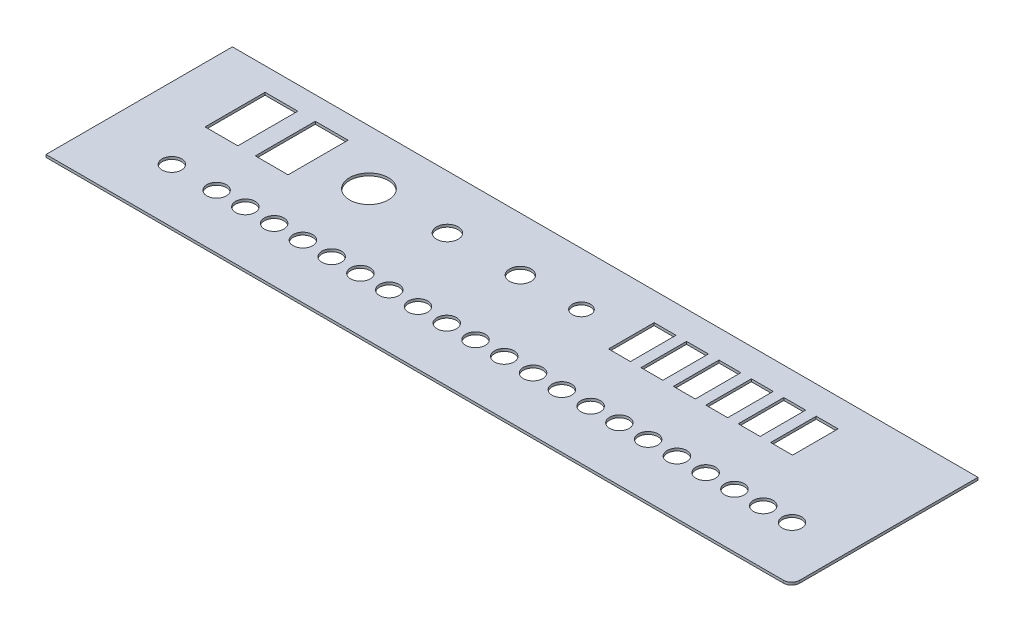
SolidWorks part; units mm, degrees
ref_plane "Front Plane" through (0, 0, 0) normal (0, 0, 1) x (1, 0, 0)
ref_plane "Top Plane" through (0, 0, 0) normal (0, 1, 0) x (1, 0, 0)
ref_plane "Right Plane" through (0, 0, 0) normal (1, 0, 0) x (0, 0, -1)
sketch "Boceto" plane through (0, 0, 0) normal (0, 1, 0) x (1, 0, 0)
  line L0 (-59.1, 30.6902) -> (-173.0029, 30.6902) construction
  line L5 (-59.1, -51.6098) -> (395.9, -51.6098) construction
  line L6 (-59.1, -51.6098) -> (-59.1, 63.3902) construction
  line L7 (-59.1, 63.3902) -> (395.9, 63.3902) construction
  line L8 (395.9, -51.6098) -> (395.9, 63.3902) construction
  line L9 (-28.6, 48.9902) -> (-8.6, 48.9902) construction
  line L10 (-28.6, 48.9902) -> (-28.6, 12.3902) construction
  line L11 (-28.6, 12.3902) -> (-8.6, 12.3902) construction
  line L12 (-8.6, 48.9902) -> (-8.6, 12.3902) construction
  line L13 (-28.6, 48.9902) -> (-8.6, 12.3902) construction
  line L14 (-28.6, 12.3902) -> (-8.6, 48.9902) construction
  line L15 (-59.1, -18.1098) -> (395.9, -18.1098) construction
  line L16 (2.4, 12.3902) -> (22.4, 12.3902) construction
  line L17 (2.4, 12.3902) -> (2.4, 48.9902) construction
  line L18 (2.4, 48.9902) -> (22.4, 48.9902) construction
  line L19 (22.4, 12.3902) -> (22.4, 48.9902) construction
  line L20 (2.4, 12.3902) -> (22.4, 48.9902) construction
  line L21 (2.4, 48.9902) -> (22.4, 12.3902) construction
  line L22 (174.9, 49.7902) -> (194.9, 49.7902) construction
  line L23 (174.9, 49.7902) -> (174.9, 11.7902) construction
  line L24 (174.9, 11.7902) -> (194.9, 11.7902) construction
  line L25 (194.9, 49.7902) -> (194.9, 11.7902) construction
  line L26 (174.9, 49.7902) -> (194.9, 11.7902) construction
  line L27 (174.9, 11.7902) -> (194.9, 49.7902) construction
  line L34 (211.4, 17.5561) -> (331, 17.5561) construction
  line L35 (211.4, 17.5561) -> (211.4, 46.5902) construction
  line L36 (211.4, 46.5902) -> (331, 46.5902) construction
  line L37 (331, 17.5561) -> (331, 46.5902) construction
  line L38 (211.4, 17.5561) -> (331, 46.5902) construction
  line L39 (211.4, 46.5902) -> (331, 17.5561) construction
  circle A0 centre (54.9, 29.6902) radius 11.1 construction
  circle A1 centre (102.75, 30.2402) radius 4.85 construction
  circle A2 centre (147.75, 30.2402) radius 4.85 construction
  circle A3 centre (-18.9, -18.1098) radius 6 construction
  circle A4 centre (8.7, -18.1098) radius 6 construction
  circle A5 centre (26.45, -18.1098) radius 6 construction
  circle A6 centre (44.2, -18.1098) radius 6 construction
  circle A7 centre (61.95, -18.1098) radius 6 construction
  circle A8 centre (79.7, -18.1098) radius 6 construction
  circle A9 centre (97.45, -18.1098) radius 6 construction
  circle A10 centre (115.2, -18.1098) radius 6 construction
  circle A11 centre (132.95, -18.1098) radius 6 construction
  circle A12 centre (150.7, -18.1098) radius 6 construction
  circle A13 centre (168.45, -18.1098) radius 6 construction
  circle A14 centre (186.2, -18.1098) radius 6 construction
  circle A15 centre (203.95, -18.1098) radius 6 construction
  circle A16 centre (221.7, -18.1098) radius 6 construction
  circle A17 centre (239.45, -18.1098) radius 6 construction
  circle A18 centre (257.2, -18.1098) radius 6 construction
  circle A19 centre (274.95, -18.1098) radius 6 construction
  circle A20 centre (292.7, -18.1098) radius 6 construction
  circle A21 centre (310.45, -18.1098) radius 6 construction
  circle A22 centre (328.2, -18.1098) radius 6 construction
  circle A23 centre (345.95, -18.1098) radius 6 construction
  circle A24 centre (363.7, -18.1098) radius 6 construction
  point P0 (0, 0)
  point P6 (-18.6, 30.6902)
  point P13 (12.4, 30.6902)
  point P24 (184.9, 30.7902)
  point P34 (271.2, 32.0731)
  point P40 (0, 0)
  point P41 (0, 0)
  dimension "D10" = 22.2
  dimension "D11" = 33.7
  dimension "D14" = 9.7
  dimension "D17" = 9.7
  dimension "D23" = 12
  dimension "D29" = 81.5
  dimension "D30" = 12
  dimension "D1" = 455
  dimension "D2" = 115
  dimension "D3" = 14.4
  dimension "D4" = 30.5
  dimension "D5" = 20
  dimension "D6" = 36.6
  dimension "D7" = 11
  dimension "D8" = 20
  dimension "D9" = 36.6
  dimension "D12" = 114
  dimension "D13" = 161.85
  dimension "D15" = 33.15
  dimension "D16" = 33.15
  dimension "D18" = 206.85
  dimension "D19" = 20
  dimension "D20" = 38
  dimension "D21" = 13.6
  dimension "D22" = 234
  dimension "D24" = 270.5
  dimension "D25" = 119.6
  dimension "D26" = 16.8
  dimension "D27" = 29.0341
  dimension "D28" = 40.2
  dimension "D31" = 27.6
  dimension "D32" = 21
sketch "Sketch4" plane through (0, 0, 0) normal (0, 1, 0) x (1, 0, 0)
  line L0 (-28.6, 48.9902) -> (-8.6, 12.3902) construction
  line L1 (-60.5474, 63.3902) -> (394.4526, 63.3902)
  line L3 (-60.5474, -51.6098) -> (391.9526, -51.6098)
  line L5 (-28.7093, 12.1902) -> (-8.4907, 12.1902)
  line L6 (-28.7093, 12.1902) -> (-28.7093, 49.1902)
  line L7 (-28.7093, 49.1902) -> (-8.4907, 49.1902)
  line L8 (-8.4907, 12.1902) -> (-8.4907, 49.1902)
  line L9 (-28.7093, 12.1902) -> (-8.4907, 49.1902) construction
  line L10 (-28.7093, 49.1902) -> (-8.4907, 12.1902) construction
  line L11 (-28.6, 12.3902) -> (-8.6, 48.9902) construction
  line L12 (2.4, 12.3902) -> (22.4, 48.9902) construction
  line L17 (2.2907, 12.1902) -> (2.2907, 49.1902)
  line L18 (2.2907, 12.1902) -> (22.5093, 12.1902)
  line L19 (22.5093, 12.1902) -> (22.5093, 49.1902)
  line L20 (2.2907, 49.1902) -> (22.5093, 49.1902)
  line L21 (102.75, 30.2402) -> (199.8359, 30.2402) construction
  line L22 (211.4, 32.0731) -> (331, 32.0731) construction
  line L23 (211.4, 17.5561) -> (211.4, 46.5902) construction
  line L24 (331, 17.5561) -> (331, 46.5902) construction
  line L25 (247.9, 46.1231) -> (247.9, 18.0231)
  line L26 (227.9, 46.1231) -> (214.4, 46.1231)
  line L27 (227.9, 46.1231) -> (227.9, 18.0231)
  line L28 (227.9, 18.0231) -> (214.4, 18.0231)
  line L29 (214.4, 46.1231) -> (214.4, 18.0231)
  line L30 (227.9, 46.1231) -> (214.4, 18.0231) construction
  line L31 (227.9, 18.0231) -> (214.4, 46.1231) construction
  line L32 (247.9, 46.1231) -> (234.4, 46.1231)
  line L33 (234.4, 46.1231) -> (234.4, 18.0231)
  line L34 (247.9, 18.0231) -> (234.4, 18.0231)
  line L35 (267.9, 46.1231) -> (267.9, 18.0231)
  line L36 (267.9, 46.1231) -> (254.4, 46.1231)
  line L37 (254.4, 46.1231) -> (254.4, 18.0231)
  line L38 (267.9, 18.0231) -> (254.4, 18.0231)
  line L39 (287.9, 46.1231) -> (287.9, 18.0231)
  line L40 (287.9, 46.1231) -> (274.4, 46.1231)
  line L41 (274.4, 46.1231) -> (274.4, 18.0231)
  line L42 (287.9, 18.0231) -> (274.4, 18.0231)
  line L43 (307.9, 46.1231) -> (307.9, 18.0231)
  line L44 (307.9, 46.1231) -> (294.4, 46.1231)
  line L45 (294.4, 46.1231) -> (294.4, 18.0231)
  line L46 (307.9, 18.0231) -> (294.4, 18.0231)
  line L47 (327.9, 46.1231) -> (327.9, 18.0231)
  line L48 (327.9, 46.1231) -> (314.4, 46.1231)
  line L49 (314.4, 46.1231) -> (314.4, 18.0231)
  line L50 (327.9, 18.0231) -> (314.4, 18.0231)
  line L52 (-60.5474, 63.3902) -> (-63.0474, 63.3902)
  line L54 (-60.5474, -51.6098) -> (-63.0474, -51.6098)
  line L55 (-63.0474, 63.3902) -> (-63.0474, -51.6098)
  line L58 (394.4526, 63.3902) -> (396.9526, 63.3902)
  line L59 (396.9526, -46.6098) -> (396.9526, 63.3902)
  circle A0 centre (54.9, 29.6902) radius 11.95
  circle A1 centre (102.75, 30.2402) radius 6.65
  circle A4 centre (147.75, 30.2402) radius 6.65
  circle A6 centre (184.9, 30.7902) radius 5.6
  circle A7 centre (-18.9, -18.1098) radius 6
  circle A8 centre (8.7, -18.1098) radius 6
  circle A9 centre (26.45, -18.1098) radius 6
  circle A10 centre (44.2, -18.1098) radius 6
  circle A11 centre (61.95, -18.1098) radius 6
  circle A12 centre (79.7, -18.1098) radius 6
  circle A13 centre (97.45, -18.1098) radius 6
  circle A14 centre (115.2, -18.1098) radius 6
  circle A15 centre (132.95, -18.1098) radius 6
  circle A16 centre (150.7, -18.1098) radius 6
  circle A17 centre (168.45, -18.1098) radius 6
  circle A18 centre (186.2, -18.1098) radius 6
  circle A19 centre (203.95, -18.1098) radius 6
  circle A20 centre (221.7, -18.1098) radius 6
  circle A21 centre (239.45, -18.1098) radius 6
  circle A22 centre (257.2, -18.1098) radius 6
  circle A23 centre (274.95, -18.1098) radius 6
  circle A24 centre (292.7, -18.1098) radius 6
  circle A25 centre (310.45, -18.1098) radius 6
  circle A26 centre (328.2, -18.1098) radius 6
  circle A27 centre (345.95, -18.1098) radius 6
  circle A28 centre (363.7, -18.1098) radius 6
  arc A29 (396.9526, -46.6098) -> (391.9526, -51.6098) centre (391.9526, -46.6098) cw
  point P6 (-18.6, 30.6902)
  point P15 (12.4, 30.6902)
  point P40 (221.15, 32.0731)
  dimension "D3" = 23.9
  dimension "D4" = 13.3
  dimension "D5" = 2
  dimension "D6" = 11.2
  dimension "D11" = 12
  dimension "D13" = 5
  dimension "D1" = 37
  dimension "D2" = 2
  dimension "D7" = 13.5
  dimension "D8" = 28.1
  dimension "D9" = 3
  dimension "D14" = 2.5
  dimension "D15" = 2.5
  dimension "D10" = 6
  dimension "D12" = 21
extrude "Boss-Extrude1" add sketch "Sketch4" along normal blind 1.6
